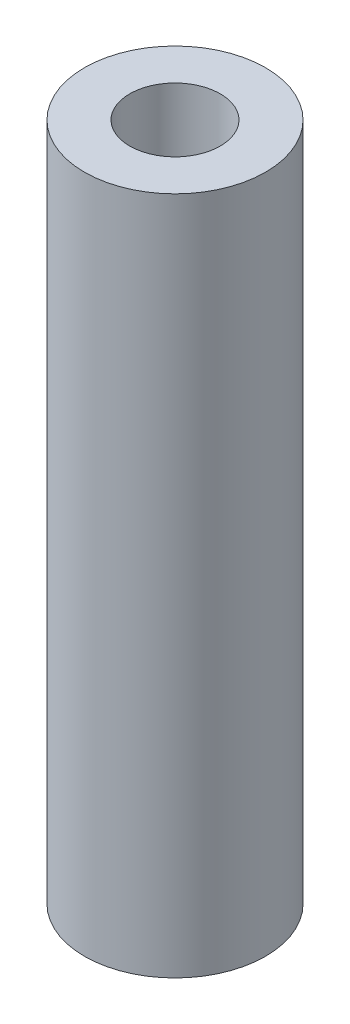
SolidWorks part; units mm, degrees
ref_plane "Front Plane" through (0, 0, 0) normal (0, 0, 1) x (1, 0, 0)
ref_plane "Top Plane" through (0, 0, 0) normal (0, 1, 0) x (1, 0, 0)
ref_plane "Right Plane" through (0, 0, 0) normal (1, 0, 0) x (0, 0, -1)
sketch "Sketch1" plane through (0, 0, 0) normal (0, 1, 0) x (1, 0, 0)
  circle A0 centre (0, 0) radius 2
  circle A1 centre (0, 0) radius 4
  dimension "D1" = 4
  dimension "D2" = 8
extrude "Boss-Extrude1" add sketch "Sketch1" along normal blind 30
